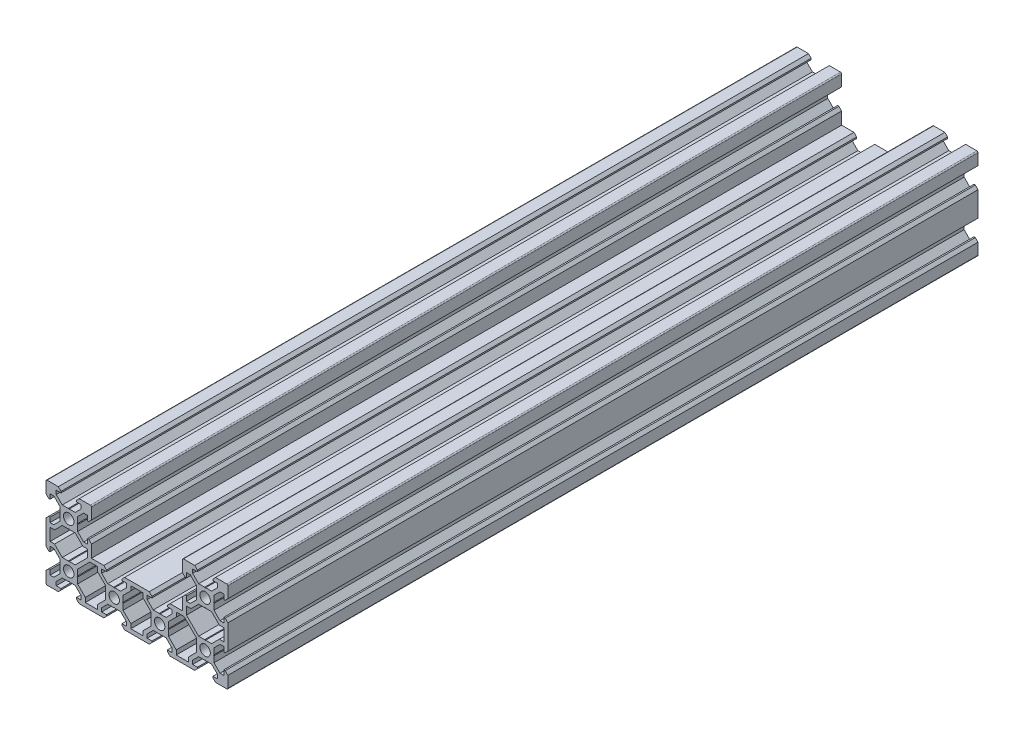
SolidWorks part; units mm, degrees
material "6063-T5"
ref_plane "Plan de face" through (0, 0, 0) normal (0, 0, 1) x (1, 0, 0)
ref_plane "Plan de dessus" through (0, 0, 0) normal (0, 1, 0) x (1, 0, 0)
ref_plane "Plan de droite" through (0, 0, 0) normal (1, 0, 0) x (0, 0, -1)
sketch "Esquisse1" plane through (0, 0, 0) normal (0, 0, 1) x (1, 0, 0)
  line L0 (-3.9, 2.8393) -> (-6.5607, 5.5)
  line L1 (-3.9, 3.9) -> (3.9, 3.9) construction
  line L2 (-3.9, 3.9) -> (-3.9, -3.9) construction
  line L3 (-3.9, -3.9) -> (3.9, -3.9) construction
  line L4 (3.9, 3.9) -> (3.9, -3.9) construction
  line L5 (-3.9, 3.9) -> (3.9, -3.9) construction
  line L6 (-3.9, -3.9) -> (3.9, 3.9) construction
  line L7 (-2.8393, 3.9) -> (-5.5, 6.5607)
  line L8 (-6.5607, 5.5) -> (-8.2, 5.5)
  line L9 (-8.2, 5.5) -> (-8.2, 3.395)
  line L10 (-8.2, 3.395) -> (-8.815, 3.395)
  line L11 (-8.815, 3.395) -> (-10, 4.58)
  line L12 (-10, 4.58) -> (-10, 9.5)
  line L13 (-4.58, 10) -> (-9.5, 10)
  line L14 (-3.395, 8.815) -> (-4.58, 10)
  line L15 (-3.395, 8.2) -> (-3.395, 8.815)
  line L16 (-5.5, 8.2) -> (-3.395, 8.2)
  line L17 (-5.5, 6.5607) -> (-5.5, 8.2)
  line L18 (0, 7.4695) -> (0, -30) construction
  line L19 (5.5, 6.5607) -> (5.5, 8.2)
  line L20 (5.5, 8.2) -> (3.395, 8.2)
  line L21 (3.395, 8.2) -> (3.395, 8.815)
  line L22 (3.395, 8.815) -> (4.58, 10)
  line L23 (4.58, 10) -> (9.5, 10)
  line L24 (10, 4.58) -> (10, 9.5)
  line L25 (8.815, 3.395) -> (10, 4.58)
  line L26 (8.2, 3.395) -> (8.815, 3.395)
  line L27 (8.2, 5.5) -> (8.2, 3.395)
  line L28 (6.5607, 5.5) -> (8.2, 5.5)
  line L29 (2.8393, 3.9) -> (5.5, 6.5607)
  line L30 (3.9, 2.8393) -> (6.5607, 5.5)
  line L31 (-2.8393, 3.9) -> (2.8393, 3.9)
  line L32 (-3.9, -2.8393) -> (-6.5607, -5.5)
  line L33 (-2.8393, -3.9) -> (-6.2393, -7.3)
  line L34 (-3.9, 2.8393) -> (-3.9, -2.8393)
  line L35 (-6.5607, -5.5) -> (-8.2, -5.5)
  line L36 (-8.2, -5.5) -> (-8.2, -3.395)
  line L37 (-8.2, -3.395) -> (-8.815, -3.395)
  line L38 (-8.815, -3.395) -> (-10, -4.58)
  line L39 (-10, -4.58) -> (-10, -15.42)
  line L40 (-6.2393, -7.3) -> (-8.2, -7.3)
  line L41 (-8.2, -7.3) -> (-8.2, -12.7)
  line L42 (30, -10) -> (-10, -10) construction
  line L43 (6.2393, -7.3) -> (8.2, -7.3)
  line L44 (8.2, -7.3) -> (8.2, -10.7393)
  line L45 (8.815, -3.395) -> (10, -4.58)
  line L46 (8.2, -3.395) -> (8.815, -3.395)
  line L47 (8.2, -5.5) -> (8.2, -3.395)
  line L48 (6.5607, -5.5) -> (8.2, -5.5)
  line L49 (2.8393, -3.9) -> (6.2393, -7.3)
  line L50 (3.9, -2.8393) -> (6.5607, -5.5)
  line L51 (30, 10) -> (-10, -30) construction
  line L52 (-2.8393, -3.9) -> (2.8393, -3.9)
  line L53 (3.9, 2.8393) -> (3.9, -2.8393)
  line L54 (-3.9, -16.1) -> (3.9, -23.9) construction
  line L55 (-3.9, -23.9) -> (3.9, -16.1) construction
  line L56 (-3.9, -23.9) -> (3.9, -23.9) construction
  line L57 (-3.9, -16.1) -> (3.9, -16.1) construction
  line L58 (-3.9, -23.9) -> (-3.9, -16.1) construction
  line L59 (3.9, -23.9) -> (3.9, -16.1) construction
  line L60 (16.1, -23.9) -> (23.9, -16.1) construction
  line L61 (-2.8393, -16.1) -> (2.8393, -16.1)
  line L62 (-6.2393, -12.7) -> (-8.2, -12.7)
  line L63 (-8.815, -16.605) -> (-10, -15.42)
  line L64 (-8.2, -16.605) -> (-8.815, -16.605)
  line L65 (-8.2, -14.5) -> (-8.2, -16.605)
  line L66 (-6.5607, -14.5) -> (-8.2, -14.5)
  line L67 (-3.9, -22.8393) -> (-3.9, -17.1607)
  line L68 (-2.8393, -16.1) -> (-6.2393, -12.7)
  line L69 (-3.9, -17.1607) -> (-6.5607, -14.5)
  line L70 (23.9, -23.9) -> (16.1, -16.1) construction
  line L71 (23.9, -16.1) -> (16.1, -16.1) construction
  line L72 (16.1, -23.9) -> (16.1, -16.1) construction
  line L73 (23.9, -23.9) -> (16.1, -23.9) construction
  line L74 (23.9, -23.9) -> (23.9, -16.1) construction
  line L75 (10, -4.58) -> (10, -10)
  line L76 (-2.8393, -23.9) -> (-5.5, -26.5607)
  line L77 (-10, -24.58) -> (-10, -29.5)
  line L78 (-8.815, -23.395) -> (-10, -24.58)
  line L79 (-8.2, -23.395) -> (-8.815, -23.395)
  line L80 (-8.2, -25.5) -> (-8.2, -23.395)
  line L81 (-6.5607, -25.5) -> (-8.2, -25.5)
  line L82 (-5.5, -26.5607) -> (-5.5, -28.2)
  line L83 (-3.9, -22.8393) -> (-6.5607, -25.5)
  line L84 (-5.5, -28.2) -> (-3.395, -28.2)
  line L85 (-3.395, -28.2) -> (-3.395, -28.815)
  line L86 (-3.395, -28.815) -> (-4.58, -30)
  line L87 (-4.58, -30) -> (-9.5, -30)
  line L88 (15.42, -10) -> (10, -10)
  line L89 (2.8393, -23.9) -> (5.5, -26.5607)
  line L90 (3.9, -22.8393) -> (7.3, -26.2393)
  line L91 (-2.8393, -23.9) -> (2.8393, -23.9)
  line L92 (30, -10) -> (30, -30) construction
  line L93 (5.5, -26.5607) -> (5.5, -28.2)
  line L94 (5.5, -28.2) -> (3.395, -28.2)
  line L95 (3.395, -28.2) -> (3.395, -28.815)
  line L96 (3.395, -28.815) -> (4.58, -30)
  line L97 (7.3, -26.2393) -> (7.3, -28.2)
  line L98 (3.9, -22.8393) -> (3.9, -17.1607)
  line L99 (22.8393, -16.1) -> (17.1607, -16.1)
  line L100 (16.1, -22.8393) -> (16.1, -17.1607)
  line L101 (17.1607, -16.1) -> (14.5, -13.4393)
  line L102 (16.1, -17.1607) -> (12.7, -13.7607)
  line L103 (14.5, -13.4393) -> (14.5, -11.8)
  line L104 (14.5, -11.8) -> (16.605, -11.8)
  line L105 (16.605, -11.8) -> (16.605, -11.185)
  line L106 (16.605, -11.185) -> (15.42, -10)
  line L107 (12.7, -11.8) -> (9.2607, -11.8)
  line L108 (12.7, -13.7607) -> (12.7, -11.8)
  line L109 (12.7, -28.2) -> (7.3, -28.2)
  line L110 (12.7, -26.2393) -> (12.7, -28.2)
  line L111 (15.42, -30) -> (4.58, -30)
  line L112 (16.605, -28.815) -> (15.42, -30)
  line L113 (16.605, -28.2) -> (16.605, -28.815)
  line L114 (14.5, -28.2) -> (16.605, -28.2)
  line L115 (14.5, -26.5607) -> (14.5, -28.2)
  line L116 (22.8393, -23.9) -> (17.1607, -23.9)
  line L117 (16.1, -22.8393) -> (12.7, -26.2393)
  line L118 (17.1607, -23.9) -> (14.5, -26.5607)
  line L119 (23.9, -22.8393) -> (23.9, -17.1607)
  line L120 (22.8393, -16.1) -> (25.5, -13.4393)
  line L121 (23.9, -17.1607) -> (27.3, -13.7607)
  line L122 (23.395, -11.8) -> (25.5, -11.8)
  line L123 (25.5, -11.8) -> (25.5, -13.4393)
  line L124 (23.395, -11.8) -> (23.395, -11.185)
  line L125 (23.395, -11.185) -> (24.58, -10)
  line L126 (24.58, -10) -> (30, -10)
  line L127 (27.3, -13.7607) -> (27.3, -11.8)
  line L128 (27.3, -11.8) -> (30, -11.8)
  line L129 (23.9, -22.8393) -> (27.3, -26.2393)
  line L130 (27.3, -26.2393) -> (27.3, -28.2)
  line L131 (27.3, -28.2) -> (30, -28.2)
  line L132 (20, -16.1) -> (20, -23.9) construction
  line L133 (10, -28.2) -> (10, -10) construction
  line L134 (30, -10) -> (30, -11.8)
  line L135 (30, -28.2) -> (30, -30)
  line L136 (2.8393, -16.1) -> (8.2, -10.7393)
  line L137 (24.58, -30) -> (30, -30)
  line L138 (23.395, -28.815) -> (24.58, -30)
  line L139 (23.395, -28.2) -> (23.395, -28.815)
  line L140 (25.5, -28.2) -> (23.395, -28.2)
  line L141 (25.5, -26.5607) -> (25.5, -28.2)
  line L142 (3.9, -17.1607) -> (9.2607, -11.8)
  line L143 (22.8393, -23.9) -> (25.5, -26.5607)
  circle A0 centre (0, 0) radius 2.3
  arc A1 (-10, 9.5) -> (-9.5, 10) centre (-9.5, 9.5) cw
  arc A2 (10, 9.5) -> (9.5, 10) centre (9.5, 9.5) ccw
  arc A3 (-10, -29.5) -> (-9.5, -30) centre (-9.5, -29.5) ccw
  circle A4 centre (0, -20) radius 2.3
  circle A7 centre (20, -20) radius 2.3
  point P62 (10, -10)
  point P78 (-8.2, -10)
  point P94 (10, -10)
  point P162 (10, -28.2)
  dimension "D1" = 4.6
  dimension "D3" = 0.5
  dimension "D2" = 1.5
  dimension "D4" = 20
  dimension "D5" = 11
  dimension "D6" = 9.16
  dimension "D7" = 6.79
  dimension "D8" = 1.8
  dimension "D9" = 4.3
  dimension "D10" = 1.5
  dimension "D11" = 6.79
  dimension "D15" = 1.8
extrude "Boss.-Extru.1" add sketch "Esquisse1" along normal blind 330
sketch "Esquisse2" plane through (0, 0, 330) normal (0, 0, 1) x (1, 0, 0)
  line L0 (0, 3.9) -> (0, -23.9) construction
  line L1 (2.8393, 3.9) -> (-2.8393, 3.9) construction
  line L2 (-2.8393, -23.9) -> (2.8393, -23.9) construction
  line L3 (-10, -10) -> (30, -10) construction
  line L4 (-10, -4.58) -> (-10, -15.42) construction
  line L5 (-0.21, 3.9) -> (0, 3.69)
  line L6 (0.21, 3.9) -> (0, 3.69)
  line L7 (-0.21, 3.9) -> (0.21, 3.9)
  line L8 (-3.9, 0) -> (3.9, 0) construction
  line L9 (-3.9, 2.8393) -> (-3.9, -2.8393) construction
  line L10 (3.9, -2.8393) -> (3.9, 2.8393) construction
  line L11 (9.8536, 9.8536) -> (-10, -10) construction
  line L12 (3.9, -0.21) -> (3.9, 0.21)
  line L13 (3.9, 0.21) -> (3.69, 0)
  line L14 (3.9, -0.21) -> (3.69, 0)
  line L15 (-9.8536, 9.8536) -> (10, -10) construction
  line L16 (0.21, -3.9) -> (0, -3.69)
  line L17 (-0.21, -3.9) -> (0, -3.69)
  line L18 (0.21, -3.9) -> (-0.21, -3.9)
  line L19 (-3.9, 0.21) -> (-3.9, -0.21)
  line L20 (-3.9, -0.21) -> (-3.69, 0)
  line L21 (-3.9, 0.21) -> (-3.69, 0)
  line L22 (-3.9, -20.21) -> (-3.69, -20)
  line L23 (-3.9, -19.79) -> (-3.69, -20)
  line L24 (-3.9, -20.21) -> (-3.9, -19.79)
  line L25 (0.21, -16.1) -> (-0.21, -16.1)
  line L26 (-0.21, -16.1) -> (0, -16.31)
  line L27 (0.21, -16.1) -> (0, -16.31)
  line L28 (3.9, -19.79) -> (3.69, -20)
  line L29 (3.9, -20.21) -> (3.69, -20)
  line L30 (3.9, -19.79) -> (3.9, -20.21)
  line L31 (-0.21, -23.9) -> (0.21, -23.9)
  line L32 (0.21, -23.9) -> (0, -23.69)
  line L33 (-0.21, -23.9) -> (0, -23.69)
  line L34 (10, -10) -> (10, -30) construction
  line L35 (4.58, -30) -> (15.42, -30) construction
  line L36 (20.21, -23.9) -> (20, -23.69)
  line L37 (19.79, -23.9) -> (20, -23.69)
  line L38 (20.21, -23.9) -> (19.79, -23.9)
  line L39 (16.1, -19.79) -> (16.1, -20.21)
  line L40 (16.1, -20.21) -> (16.31, -20)
  line L41 (16.1, -19.79) -> (16.31, -20)
  line L42 (19.79, -16.1) -> (20, -16.31)
  line L43 (20.21, -16.1) -> (20, -16.31)
  line L44 (19.79, -16.1) -> (20.21, -16.1)
  line L45 (23.9, -20.21) -> (23.9, -19.79)
  line L46 (23.9, -19.79) -> (23.69, -20)
  line L47 (23.9, -20.21) -> (23.69, -20)
  arc A0 (10, 9.5) -> (9.5, 10) centre (9.5, 9.5) ccw construction
  arc A1 (-9.5, 10) -> (-10, 9.5) centre (-9.5, 9.5) ccw construction
  dimension "D1" = 45
  dimension "D2" = 0.42
extrude "Enlèv. mat.-Extru.1" cut sketch "Esquisse2" against normal through all
mirror "Symétrie1" about plane through (30, -10, 330) normal (-1, 0, 0) of "Enlèv. mat.-Extru.1", "Boss.-Extru.1"
